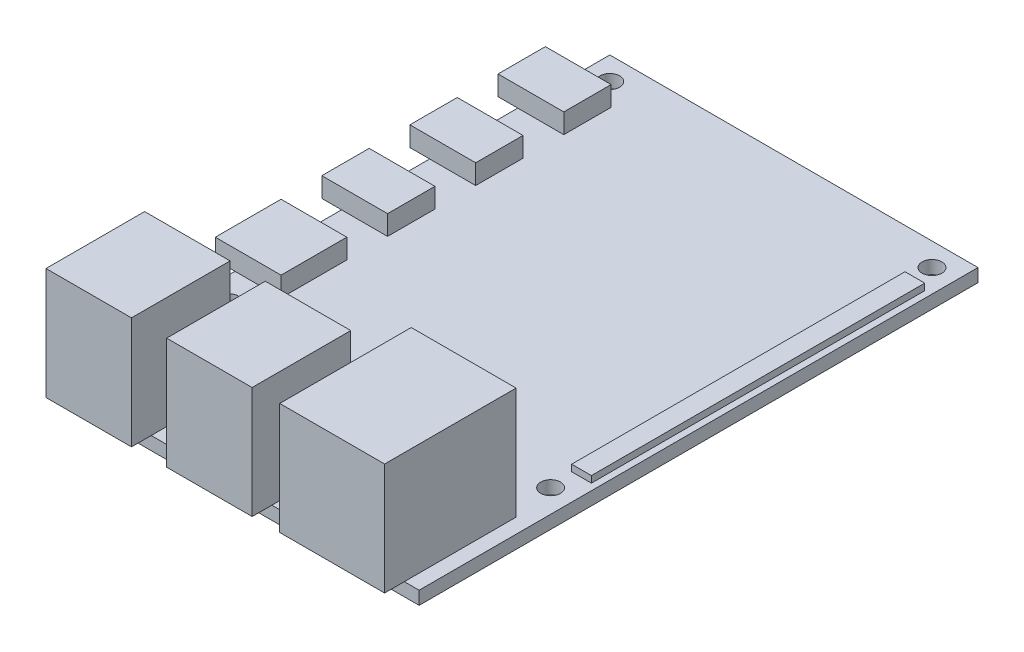
SolidWorks part; units mm, degrees
ref_plane "Front Plane" through (0, 0, 0) normal (0, 0, 1) x (1, 0, 0)
ref_plane "Top Plane" through (0, 0, 0) normal (0, 1, 0) x (1, 0, 0)
ref_plane "Right Plane" through (0, 0, 0) normal (1, 0, 0) x (0, 0, -1)
sketch "Sketch1" plane through (0, 0, 0) normal (0, 1, 0) x (1, 0, 0)
  line L1 (-28, -42.5) -> (28, -42.5)
  line L2 (-28, -42.5) -> (-28, 42.5)
  line L3 (-28, 42.5) -> (28, 42.5)
  line L4 (28, -42.5) -> (28, 42.5)
  line L5 (-28, -42.5) -> (28, 42.5) construction
  line L6 (-28, 42.5) -> (28, -42.5) construction
  line L7 (-24.5, 39) -> (24.5, 39) construction
  line L8 (-24.5, 39) -> (-24.5, -19) construction
  line L9 (-24.5, -19) -> (24.5, -19) construction
  line L10 (24.5, 39) -> (24.5, -19) construction
  circle A0 centre (-24.5, 39) radius 1.5
  circle A1 centre (24.5, 39) radius 1.5
  circle A2 centre (-24.5, -19) radius 1.5
  circle A3 centre (24.5, -19) radius 1.5
  point P0 (0, 0)
  point P10 (0, 39)
  dimension "D6" = 3
  dimension "D1" = 56
  dimension "D2" = 85
  dimension "D3" = 49
  dimension "D4" = 58
  dimension "D5" = 3.5
extrude "Boss-Extrude1" add sketch "Sketch1" along normal blind 2
sketch "Sketch2" plane through (0, 2, 0) normal (0, 1, 0) x (1, 0, 0)
  line L0 (28, 42.5) -> (-28, 42.5) construction
  line L1 (27, 35.4) -> (24, 35.4)
  line L2 (27, 35.4) -> (27, -15.3)
  line L3 (27, -15.3) -> (24, -15.3)
  line L4 (24, 35.4) -> (24, -15.3)
  line L5 (-28, -42.5) -> (28, -42.5) construction
  line L6 (28, -42.5) -> (28, 42.5) construction
  dimension "D1" = 7.1
  dimension "D2" = 27.2
  dimension "D3" = 3
  dimension "D4" = 1
extrude "Boss-Extrude2" add sketch "Sketch2" along normal blind 1
sketch "Sketch3" plane through (0, 2, 0) normal (0, 1, 0) x (1, 0, 0)
  line L0 (28, -42.5) -> (28, 42.5) construction
  line L1 (-25.75, -30.5) -> (-12.75, -30.5)
  line L2 (-25.75, -30.5) -> (-25.75, -45.5)
  line L3 (-25.75, -45.5) -> (-12.75, -45.5)
  line L4 (-12.75, -30.5) -> (-12.75, -45.5)
  line L5 (-7.4, -30.5) -> (5.6, -30.5)
  line L6 (-7.4, -30.5) -> (-7.4, -45.5)
  line L7 (-7.4, -45.5) -> (5.6, -45.5)
  line L8 (5.6, -30.5) -> (5.6, -45.5)
  line L9 (9.8, -25.5) -> (25.75, -25.5)
  line L10 (9.8, -25.5) -> (9.8, -45.5)
  line L11 (9.8, -45.5) -> (25.75, -45.5)
  line L12 (25.75, -25.5) -> (25.75, -45.5)
  line L13 (-28, 42.5) -> (-28, -42.5) construction
  line L14 (-28, -42.5) -> (28, -42.5) construction
  dimension "D1" = 2.25
  dimension "D2" = 2.25
  dimension "D3" = 20.6
  dimension "D4" = 37.8
  dimension "D5" = 13
  dimension "D6" = 15
  dimension "D7" = 20
  dimension "D8" = 3
extrude "Boss-Extrude3" add sketch "Sketch3" along normal blind 17
sketch "Sketch4" plane through (0, 2, 0) normal (0, 1, 0) x (1, 0, 0)
  line L0 (-28, 42.5) -> (-28, -42.5) construction
  line L1 (-31, 35.7) -> (-21, 35.7)
  line L2 (-31, 35.7) -> (-31, 28.5)
  line L3 (-31, 28.5) -> (-21, 28.5)
  line L4 (-21, 35.7) -> (-21, 28.5)
  line L5 (-31, 8.9) -> (-21, 8.9)
  line L6 (-31, 8.9) -> (-31, 1.7)
  line L7 (-31, 1.7) -> (-21, 1.7)
  line L8 (-21, 8.9) -> (-21, 1.7)
  line L9 (-31, -4.5) -> (-21, -4.5)
  line L10 (-31, -4.5) -> (-31, -14.5)
  line L11 (-31, -14.5) -> (-21, -14.5)
  line L12 (-21, -4.5) -> (-21, -14.5)
  line L13 (28, 42.5) -> (-28, 42.5) construction
  line L14 (-31, 28.5) -> (-31, 22.3) construction
  line L15 (-31, 22.3) -> (-21, 22.3)
  line L16 (-31, 22.3) -> (-31, 15.1)
  line L17 (-31, 15.1) -> (-21, 15.1)
  line L18 (-21, 22.3) -> (-21, 15.1)
  line L19 (-31, 15.1) -> (-31, 8.9) construction
  line L20 (-31, 1.7) -> (-31, -4.5) construction
  point P16 (-31, -9.5)
  dimension "D1" = 3
  dimension "D2" = 6.8
  dimension "D3" = 7.2
  dimension "D4" = 11.2
  dimension "D5" = 10
  dimension "D6" = 10
extrude "Boss-Extrude4" add sketch "Sketch4" along normal blind 3
